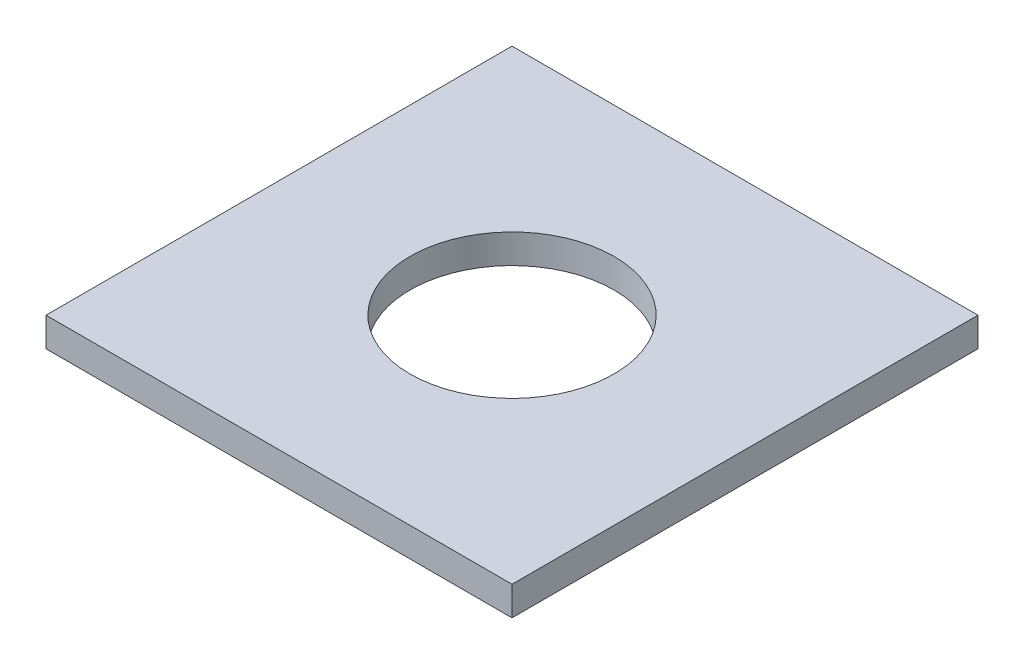
SolidWorks part; units mm, degrees
material "Maple"
ref_plane "Front Plane" through (0, 0, 0) normal (0, 0, 1) x (1, 0, 0)
ref_plane "Top Plane" through (0, 0, 0) normal (0, 1, 0) x (1, 0, 0)
ref_plane "Right Plane" through (0, 0, 0) normal (1, 0, 0) x (0, 0, -1)
sketch "Sketch1" plane through (0, 0, 0) normal (0, 1, 0) x (1, 0, 0)
  line L0 (101.6, 50.8) -> (0, 50.8) construction
  line L1 (0, 0) -> (101.6, 0)
  line L2 (0, 0) -> (0, 101.6)
  line L3 (0, 101.6) -> (101.6, 101.6)
  line L4 (101.6, 0) -> (101.6, 101.6)
  circle A0 centre (50.8, 50.8) radius 22.225
  dimension "D3" = 44.45
  dimension "D1" = 101.6
  dimension "D2" = 101.6
extrude "Boss-Extrude1" add sketch "Sketch1" along normal blind 6.35
